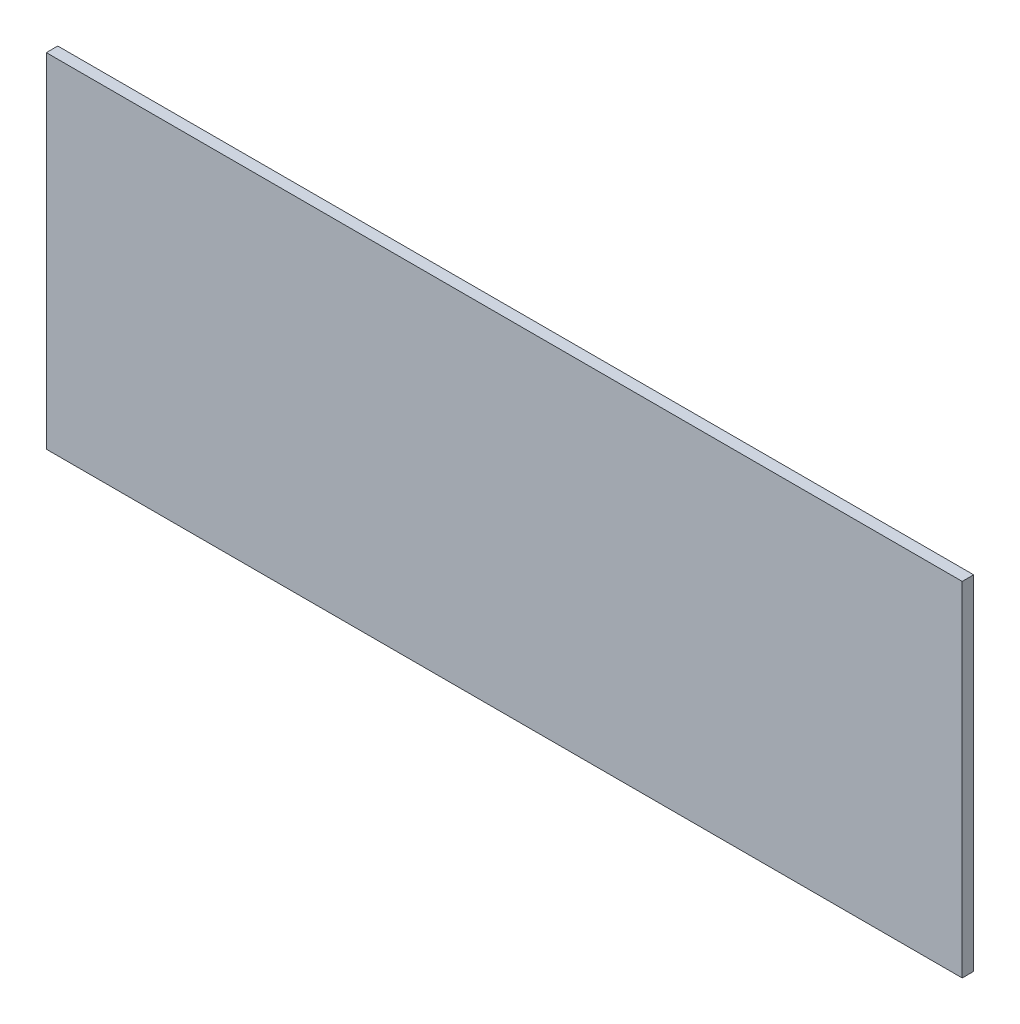
SolidWorks part; units mm, degrees
ref_plane "Front Plane" through (0, 0, 0) normal (0, 0, 1) x (1, 0, 0)
ref_plane "Top Plane" through (0, 0, 0) normal (0, 1, 0) x (1, 0, 0)
ref_plane "Right Plane" through (0, 0, 0) normal (1, 0, 0) x (0, 0, -1)
sketch "Sketch1" plane through (0, 0, 0) normal (0, 0, 1) x (1, 0, 0)
  line L1 (-2000, 750) -> (2000, 750)
  line L2 (-2000, 750) -> (-2000, -750)
  line L3 (-2000, -750) -> (2000, -750)
  line L4 (2000, 750) -> (2000, -750)
  line L5 (-2000, 750) -> (2000, -750) construction
  line L6 (-2000, -750) -> (2000, 750) construction
  point P0 (0, 0)
  dimension "D1" = 4000
  dimension "D2" = 1500
extrude "Boss-Extrude1" add sketch "Sketch1" along normal blind 50
